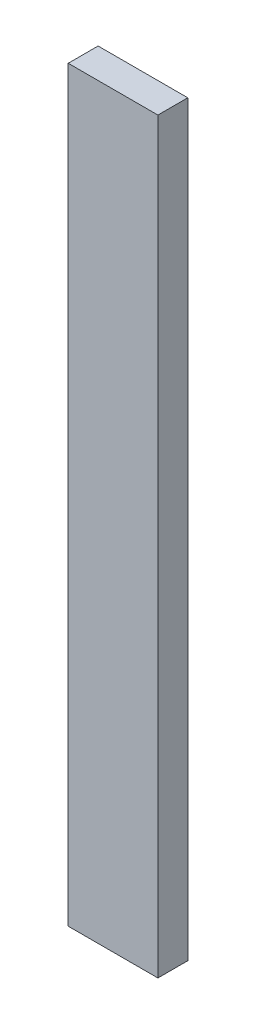
SolidWorks part; units mm, degrees
ref_plane "Front Plane" through (0, 0, 0) normal (1, 0, 0) x (0, 1, 0)
ref_plane "Top Plane" through (0, 0, 0) normal (0, 0, 1) x (0, 1, 0)
ref_plane "Right Plane" through (0, 0, 0) normal (0, 1, 0) x (-1, 0, 0)
sketch "Sketch1" plane through (0, 0, 0) normal (0, 0, 1) x (0, 1, 0)
  line L1 (0, 0) -> (25, 0)
  line L2 (0, 0) -> (0, 3)
  line L3 (0, 3) -> (25, 3)
  line L4 (25, 0) -> (25, 3)
  dimension "D1" = 25
  dimension "D2" = 3
extrude "Boss-Extrude1" add sketch "Sketch1" along normal blind 1
